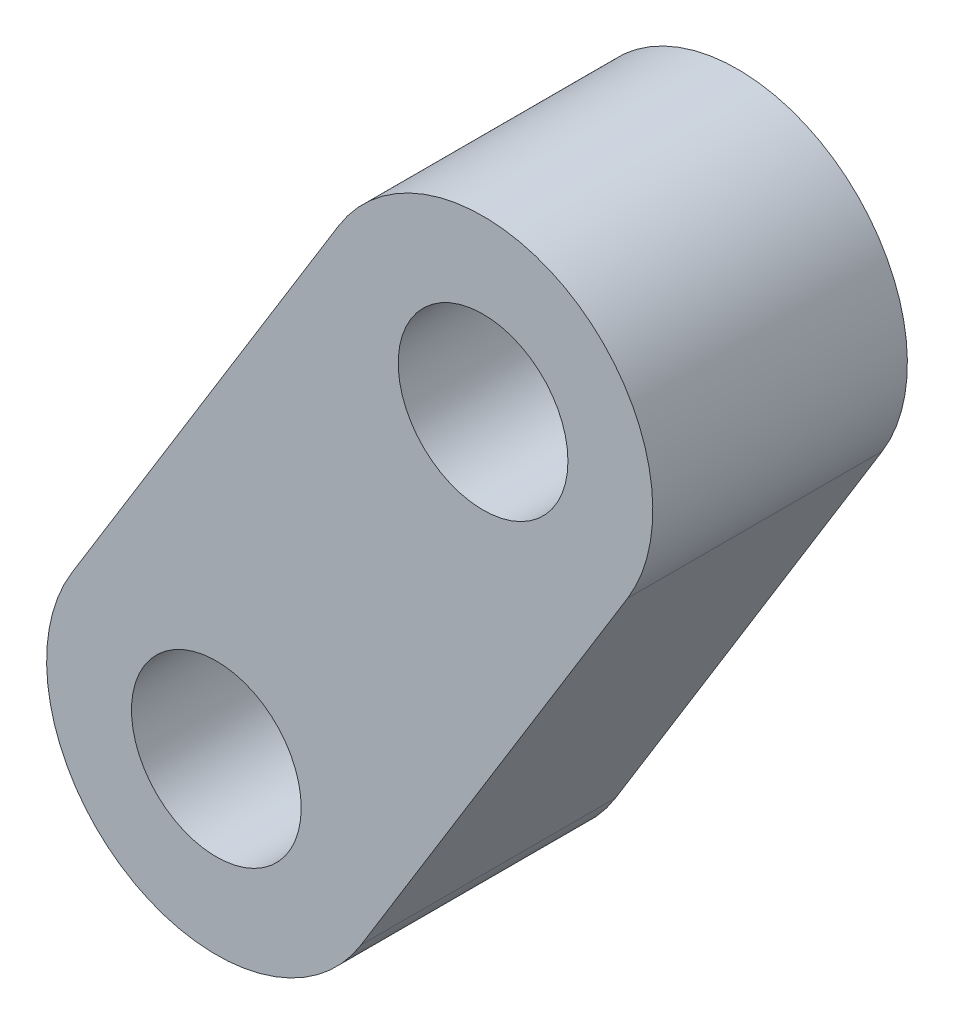
SolidWorks part; units mm, degrees
ref_plane "Front Plane" through (0, 0, 0) normal (0, 0, 1) x (1, 0, 0)
ref_plane "Top Plane" through (0, 0, 0) normal (0, 1, 0) x (1, 0, 0)
ref_plane "Right Plane" through (0, 0, 0) normal (1, 0, 0) x (0, 0, -1)
sketch "Sketch1" plane through (0, 0, 0) normal (0, 0, 1) x (1, 0, 0)
  line L0 (0.8267, -6.3469) -> (3.9698, -1.2361) construction
  line L1 (-0.8769, -5.2993) -> (2.2662, -0.1884)
  line L2 (2.5304, -7.3946) -> (5.6734, -2.2838)
  arc A0 (-0.8769, -5.2993) -> (2.5304, -7.3946) centre (0.8267, -6.3469) ccw
  arc A1 (5.6734, -2.2838) -> (2.2662, -0.1884) centre (3.9698, -1.2361) ccw
  circle A2 centre (0.8267, -6.3469) radius 1
  circle A3 centre (3.9698, -1.2361) radius 1
  point P4 (2.3983, -3.7915)
  dimension "D3" = 2
  dimension "D4" = 2
  dimension "D1" = 6
  dimension "D2" = 4
extrude "Boss-Extrude1" add sketch "Sketch1" along normal blind 3
